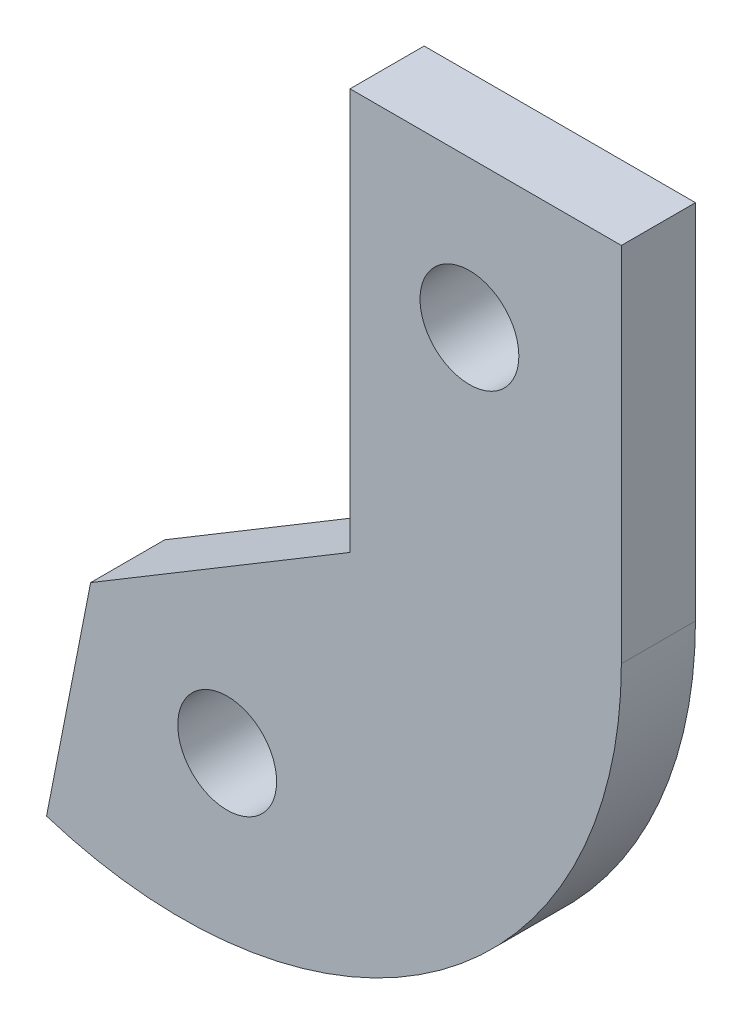
SolidWorks part; units mm, degrees
ref_plane "Płaszczyzna przednia" through (0, 0, 0) normal (0, 0, 1) x (1, 0, 0)
ref_plane "Płaszczyzna górna" through (0, 0, 0) normal (0, 1, 0) x (1, 0, 0)
ref_plane "Płaszczyzna prawa" through (0, 0, 0) normal (1, 0, 0) x (0, 0, -1)
sketch "Sketch2" plane through (0, 0, 0) normal (0, 0, 1) x (-1, 0, 0)
  line L3 (-9.018, -7.3323) -> (-20, -7.3323)
  line L4 (-20, 7.3323) -> (-20, -7.3323)
  line L6 (-9.018, 8.9202) -> (-9.018, -7.3323)
  line L8 (-9.018, 8.9202) -> (1.4825, 15.2278)
  line L9 (3.4681, 24.9079) -> (0, 8) construction
  line L10 (1.4825, 15.2278) -> (3.2672, 24.3059)
  circle A2 centre (-13.851, -1.3792) radius 2
  arc A3 (-20, 7.3323) -> (3.2672, 24.3059) centre (-2.1752, 7.3323) cw
  circle A6 centre (-4.0453, 18.4434) radius 2
  dimension "D2" = 4
  dimension "D3" = 4
  dimension "D1" = 17.8248
  dimension "D4" = 14.6646
extrude "Boss-Extrude1" add sketch "Sketch2" along normal blind 3
